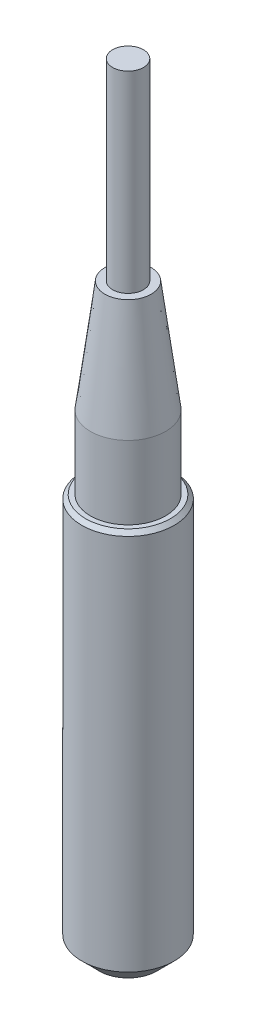
SolidWorks part; units mm, degrees
ref_plane "Alzado" through (0, 0, 0) normal (0, 0, 1) x (1, 0, 0)
ref_plane "Planta" through (0, 0, 0) normal (0, 1, 0) x (1, 0, 0)
ref_plane "Vista lateral" through (0, 0, 0) normal (1, 0, 0) x (0, 0, -1)
sketch "Croquis1" plane through (0, 0, 0) normal (0, 0, 1) x (1, 0, 0)
  line L0 (0, 0) -> (0, 87.8877) construction
  line L1 (12, 87.8877) -> (12, -11.1123)
  line L2 (0, -15.6123) -> (7.5, -15.6123)
  line L3 (7.5, -15.6123) -> (12, -11.1123)
  line L4 (12, 87.8877) -> (9.75, 87.8877)
  line L7 (0, -15.6123) -> (0, 87.8877)
  line L8 (0, 87.8877) -> (0, -15.6123)
  line L9 (9.75, 87.8877) -> (0, 87.8877)
  line L10 (0, 136.8877) -> (0, 1259.0807) construction
  dimension "D1" = 12
  dimension "D2" = 99
  dimension "D3" = 4.5
  dimension "D4" = 7.5
  dimension "D5" = 9.75
revolve "Revolución1" add sketch "Croquis1" angle 360 about L0
chamfer "Chaflán2" distance 1 angle 45 1 edges at (0, 87.8877, -12)
sketch "Croquis2" plane through (0, 0, 0) normal (0, 0, 1) x (1, 0, 0)
  line L0 (0, 87.8877) -> (9.75, 87.8877)
  line L1 (11, 87.8877) -> (-11, 87.8877) construction
  line L2 (4, 135.8877) -> (6, 135.8877)
  line L3 (9.75, 87.8877) -> (9.75, 106.8877)
  line L4 (6, 135.8877) -> (9.75, 106.8877)
  line L5 (0, 135.8877) -> (0, 87.8877)
  line L6 (4, 135.8877) -> (4, 185.8877)
  line L7 (4, 185.8877) -> (0, 185.8877)
  line L8 (0, 185.8877) -> (0, 135.8877)
  dimension "D1" = 9.75
  dimension "D2" = 19
  dimension "D3" = 6
  dimension "D4" = 29
  dimension "D5" = 4
  dimension "D6" = 50
revolve "Revolución2" add sketch "Croquis2" angle 360 about L5
